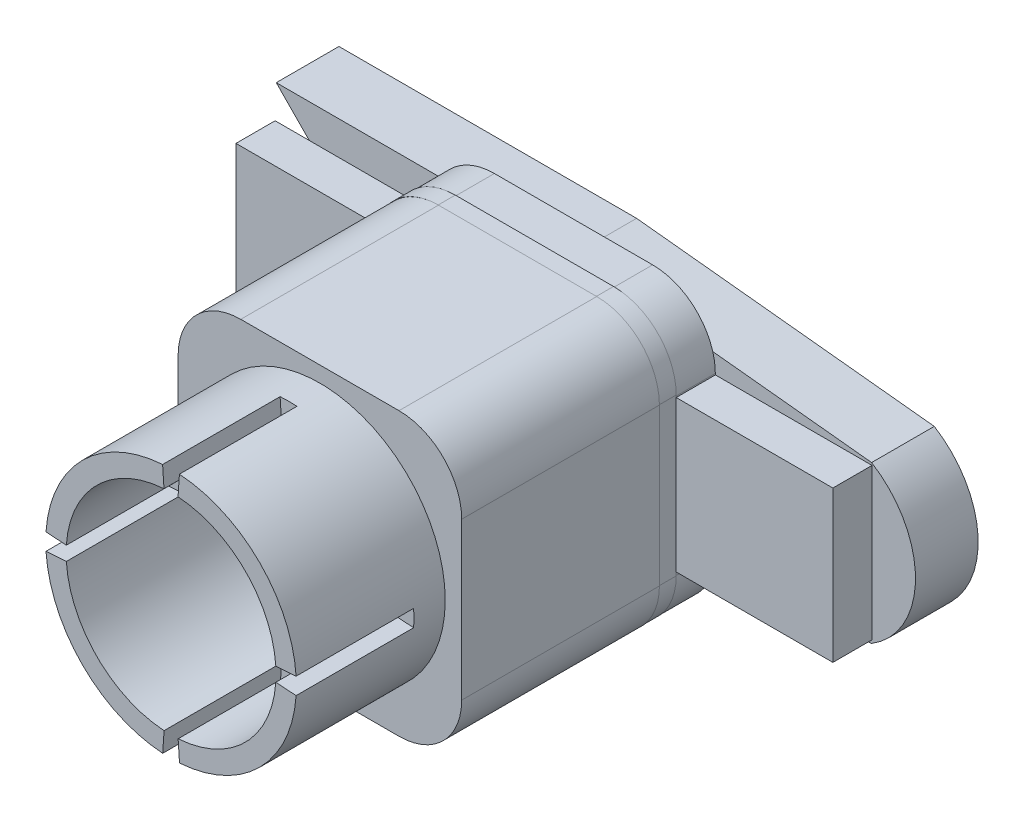
SolidWorks part; units mm, degrees
ref_plane "Front Plane" through (0, 0, 0) normal (0, 0, 1) x (1, 0, 0)
ref_plane "Top Plane" through (0, 0, 0) normal (0, 1, 0) x (1, 0, 0)
ref_plane "Right Plane" through (0, 0, 0) normal (1, 0, 0) x (0, 0, -1)
sketch "Sketch1" plane through (0, 0, 0) normal (0, 0, 1) x (1, 0, 0)
  line L12 (-5.05, 9.0001) -> (5.05, 9.0001)
  line L13 (-9.05, 5.0001) -> (-9.05, -5.0001)
  line L14 (-5.05, -9.0001) -> (5.05, -9.0001)
  line L15 (9.05, 5.0001) -> (9.05, -5.0001)
  line L16 (-9.05, 9.0001) -> (9.05, -9.0001) construction
  line L17 (-9.05, -9.0001) -> (9.05, 9.0001) construction
  arc A4 (-9.05, -5.0001) -> (-5.05, -9.0001) centre (-5.05, -5.0001) ccw
  arc A5 (5.05, -9.0001) -> (9.05, -5.0001) centre (5.05, -5.0001) ccw
  arc A6 (5.05, 9.0001) -> (9.05, 5.0001) centre (5.05, 5.0001) cw
  arc A7 (-5.05, 9.0001) -> (-9.05, 5.0001) centre (-5.05, 5.0001) ccw
  point P0 (0, 0)
  dimension "D2" = 4
  dimension "D1" = 9.05
extrude "Boss-Extrude1" add sketch "Sketch1" along normal blind 2
sketch "Sketch2" plane through (0, 0, 0) normal (0, 0, 1) x (1, 0, 0)
  line L0 (-5.05, 9.0001) -> (5.05, 9.0001)
  line L1 (-9.05, 5.0001) -> (-9.05, -5.0001)
  line L2 (-5.05, -9.0001) -> (5.05, -9.0001)
  line L3 (9.05, 5.0001) -> (9.05, -5.0001)
  line L4 (-9.05, 9.0001) -> (9.05, -9.0001) construction
  line L5 (-9.05, -9.0001) -> (9.05, 9.0001) construction
  arc A0 (-9.05, -5.0001) -> (-5.05, -9.0001) centre (-5.05, -5.0001) ccw
  arc A1 (5.05, -9.0001) -> (9.05, -5.0001) centre (5.05, -5.0001) ccw
  arc A2 (5.05, 9.0001) -> (9.05, 5.0001) centre (5.05, 5.0001) cw
  arc A3 (-5.05, 9.0001) -> (-9.05, 5.0001) centre (-5.05, 5.0001) ccw
  point P0 (0, 0)
  dimension "D2" = 4
  dimension "D1" = 9.05
extrude "Boss-Extrude2" add sketch "Sketch2" along normal blind 11.02
sketch "Sketch3" plane through (0, 0, 11.02) normal (0, 0, 1) x (1, 0, 0)
  line L1 (-5.05, 9.0001) -> (5.05, 9.0001)
  line L2 (-9.05, 5.0001) -> (-9.05, -5.0001)
  line L3 (-5.05, -9.0001) -> (5.05, -9.0001)
  line L4 (9.05, 5.0001) -> (9.05, -5.0001)
  line L5 (-9.05, 9.0001) -> (9.05, -9.0001) construction
  line L6 (-9.05, -9.0001) -> (9.05, 9.0001) construction
  arc A0 (-9.05, -5.0001) -> (-5.05, -9.0001) centre (-5.05, -5.0001) ccw
  arc A1 (5.05, -9.0001) -> (9.05, -5.0001) centre (5.05, -5.0001) ccw
  arc A2 (5.05, 9.0001) -> (9.05, 5.0001) centre (5.05, 5.0001) cw
  arc A3 (-5.05, 9.0001) -> (-9.05, 5.0001) centre (-5.05, 5.0001) ccw
  point P0 (0, 0)
  dimension "D2" = 4
  dimension "D1" = 9.05
extrude "Boss-Extrude3" add sketch "Sketch3" along normal blind 1.6
sketch "Sketch4" plane through (0, 0, 12.62) normal (0, 0, 1) x (1, 0, 0)
  circle A1 centre (0, 0) radius 8
  dimension "D2" = 16
extrude "Boss-Extrude4" add sketch "Sketch4" along normal blind 9.5
sketch "Sketch5" plane through (0, 0, 12.62) normal (0, 0, 1) x (1, 0, 0)
  circle A0 centre (0, 0) radius 6.65
  dimension "D1" = 13.3
extrude "Cut-Extrude1" cut sketch "Sketch5" along normal blind 20
sketch "Sketch12" plane through (0, 0, 0) normal (0, 0, -1) x (-1, 0, 0)
  line L0 (-5.0274, 8.9973) -> (5.0726, 8.9973)
  line L1 (-9.0274, 4.9973) -> (-9.0274, -5.0029)
  line L2 (-5.0274, -9.0029) -> (5.0726, -9.0029)
  line L3 (9.0726, 4.9973) -> (9.0726, -5.0029)
  line L4 (-9.0274, 8.9973) -> (9.0726, -9.0029) construction
  line L5 (-9.0274, -9.0029) -> (9.0726, 8.9973) construction
  arc A0 (-9.0274, -5.0029) -> (-5.0274, -9.0029) centre (-5.0274, -5.0029) ccw
  arc A1 (5.0726, -9.0029) -> (9.0726, -5.0029) centre (5.0726, -5.0029) ccw
  arc A2 (5.0726, 8.9973) -> (9.0726, 4.9973) centre (5.0726, 4.9973) cw
  arc A3 (-5.0274, 8.9973) -> (-9.0274, 4.9973) centre (-5.0274, 4.9973) ccw
  point P0 (0.0226, -0.0028)
  dimension "D2" = 4
  dimension "D1" = 9.05
extrude "Boss-Extrude5" add sketch "Sketch12" along normal blind 1.095 contours L0 A2 L3 A1 L2 A0 L1 A3
sketch "Sketch13" plane through (0, 0, 0) normal (0, 0, 1) x (1, 0, 0)
  circle A0 centre (0, 0) radius 6.7
  dimension "D1" = 13.4
extrude "Cut-Extrude3" cut sketch "Sketch13" against normal mid plane 60
sketch "Sketch15" plane through (0, 0, 22.12) normal (0, 0, 1) x (1, 0, 0)
  line L1 (-0.5528, 8.1871) -> (-0.0028, 0.0033)
  line L3 (0.5472, 8.1871) -> (-0.0028, 0.0033)
  line L4 (-0.5528, 8.1871) -> (-0.626, 9.0001)
  line L5 (5.05, 9.0001) -> (-5.05, 9.0001) construction
  line L6 (-0.626, 9.0001) -> (0.6172, 9.0001)
  line L7 (0.6172, 9.0001) -> (0.5472, 8.1871)
  dimension "D3" = 0.0732
  dimension "D4" = 0.07
extrude "Cut-Extrude4" cut sketch "Sketch15" against normal blind 7.5 contours L1 L3 L7 L6 L4
pattern_circular "CirPattern2" count 4 over 360 about axis through (0, 0, 0) along (0, 0, 1) of "Cut-Extrude4"
sketch "Sketch16" plane through (0, 0, -1.095) normal (0, 0, -1) x (-1, 0, 0)
  line L4 (-5.0236, 8.9395) -> (5.0767, 8.9395)
  line L6 (-5.0234, -8.9918) -> (5.0766, -8.9918)
  line L12 (-9.0234, 9.0084) -> (9.0766, -8.9918) construction
  line L13 (-9.0234, -8.9918) -> (9.0766, 9.0084) construction
  line L14 (0.0266, 0.0083) -> (0.0266, 11.7541) construction
  line L19 (-9.0274, 4.8569) -> (-19.0274, 4.8569)
  line L20 (-9.0274, 4.9973) -> (-9.0274, -5.0029) construction
  line L27 (-19.0274, 4.8569) -> (-19.0274, -4.7841)
  line L28 (-19.0274, -4.7841) -> (-9.0274, -4.7841)
  line L29 (-9.0274, 4.8569) -> (-9.0236, 4.9395)
  line L30 (-9.0274, -4.7841) -> (-9.0234, -4.9857)
  line L34 (9.0726, 4.8569) -> (19.0726, 4.8569)
  line L35 (9.0726, 4.9973) -> (9.0726, -5.0029) construction
  line L36 (19.0726, 4.8569) -> (19.0726, -4.8255)
  line L37 (19.0726, -4.8255) -> (9.0726, -4.8255)
  line L38 (9.0726, -4.8255) -> (9.0766, -4.9857)
  line L39 (9.0726, 4.8569) -> (9.0767, 4.9395)
  arc A6 (-9.0234, -4.9857) -> (-5.0234, -8.9918) centre (-5.0234, -4.9918) ccw
  arc A7 (5.0766, -8.9918) -> (9.0766, -4.9857) centre (5.0766, -4.9918) ccw
  arc A8 (5.0767, 8.9395) -> (9.0767, 4.9395) centre (5.0767, 4.9395) cw
  arc A9 (-5.0236, 8.9395) -> (-9.0236, 4.9395) centre (-5.0236, 4.9395) ccw
  point P0 (0.0266, 0.0083)
  point P17 (0.0266, 0.0083)
  point P23 (-13.5773, 0)
  point P32 (13.4528, 0.0083)
  point P34 (13.4528, 0.0083)
  dimension "D2" = 4
  dimension "D3" = 10
  dimension "D1" = 10
extrude "Boss-Extrude6" add sketch "Sketch16" along normal blind 2.5 separate body
sketch "Sketch17" plane through (0, 0, -3.595) normal (0, 0, -1) x (-1, 0, 0)
  line L0 (0, 7) -> (-19, 5)
  line L1 (-19, -5) -> (0, -7)
  line L2 (0, -7) -> (19, -7)
  line L3 (0, 7) -> (19, 7)
  line L4 (0, 3.7) -> (-16, 2.2)
  line L5 (-16, -2.2) -> (0, -3.7)
  line L6 (0, -3.7) -> (16, -3.95)
  line L7 (0, 3.7) -> (16, 3.95)
  line L8 (19, 7) -> (16, 3.95)
  line L9 (16, -3.95) -> (19, -7)
  arc A1 (-19, 5) -> (-19, -5) centre (-15.9375, 0) ccw
  arc A4 (-16, 2.2) -> (-16, -2.2) centre (-15, 0) ccw
  point P2 (16, 3.7)
  dimension "D2" = 2.2
  dimension "D3" = 2
  dimension "D4" = 2
  dimension "D5" = 0
  dimension "D6" = 16
  dimension "D7" = 1.5
  dimension "D8" = 1.5
  dimension "D9" = 19
  dimension "D10" = 19
  dimension "D11" = 2.2
  dimension "D12" = 5
  dimension "D13" = 5
  dimension "16" = 16
  dimension "D14" = 19
  dimension "D15" = 16
  dimension "D16" = 16
  dimension "D17" = 19
  dimension "D18" = 0
  dimension "D19" = 0
  dimension "D20" = 0
  dimension "D21" = 0
  dimension "D22" = 0
  dimension "D23" = 0.25
  dimension "D24" = 0.25
extrude "Boss-Extrude7" add sketch "Sketch17" along normal blind 4
